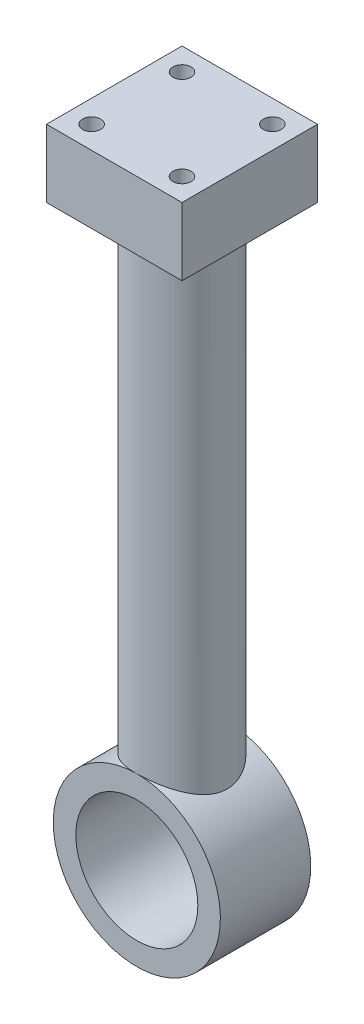
SolidWorks part; units mm, degrees
ref_plane "前视基准面" through (0, 0, 0) normal (0, 0, 1) x (1, 0, 0)
ref_plane "上视基准面" through (0, 0, 0) normal (0, 1, 0) x (1, 0, 0)
ref_plane "右视基准面" through (0, 0, 0) normal (1, 0, 0) x (0, 0, -1)
sketch "草图1" plane through (0, 0, 0) normal (0, 0, 1) x (1, 0, 0)
  circle A0 centre (0, 0) radius 18.5
  circle A1 centre (0, 0) radius 13.5
  dimension "D1" = 37
  dimension "D2" = 27
extrude "凸台-拉伸1" add sketch "草图1" along normal mid plane 20
ref_plane "基准面1" through (0, 123, 0) normal (0, 1, 0) x (1, 0, 0)
sketch "草图3" plane through (0, 123, 0) normal (0, 1, 0) x (1, 0, 0)
  circle A0 centre (0, 0) radius 10
  dimension "D1" = 20
extrude "凸台-拉伸2" add sketch "草图3" against normal up to surface (104.5 mm away)
sketch "草图4" plane through (0, 123, 0) normal (0, 1, 0) x (1, 0, 0)
  line L1 (-15, 15) -> (15, 15)
  line L2 (-15, 15) -> (-15, -15)
  line L3 (-15, -15) -> (15, -15)
  line L4 (15, 15) -> (15, -15)
  line L5 (0, -15) -> (0, 15) construction
  line L6 (-15, 0) -> (15, 0) construction
  point P0 (0, 0)
  dimension "D1" = 30
  dimension "30" = 30
extrude "凸台-拉伸3" add sketch "草图4" along normal blind 15
sketch "草图5" plane through (0, 138, 0) normal (0, 1, 0) x (1, 0, 0)
  line L1 (-10, 10) -> (10, 10) construction
  line L2 (-10, 10) -> (-10, -10) construction
  line L3 (-10, -10) -> (10, -10) construction
  line L4 (10, 10) -> (10, -10) construction
  line L5 (0, -10) -> (0, 10) construction
  line L6 (-10, 0) -> (10, 0) construction
  circle A0 centre (-10, 10) radius 2
  circle A1 centre (10, 10) radius 2
  circle A2 centre (-10, -10) radius 2
  circle A3 centre (10, -10) radius 2
  point P0 (0, 0)
  dimension "D3" = 4
  dimension "D1" = 20
  dimension "D2" = 20
extrude "切除-拉伸1" cut sketch "草图5" against normal blind 15
sketch "草图6" plane through (0, 123, 0) normal (0, -1, 0) x (1, 0, 0)
  line L1 (10, 10) -> (-10, 10) construction
  line L2 (10, 10) -> (10, -10) construction
  line L3 (10, -10) -> (-10, -10) construction
  line L4 (-10, 10) -> (-10, -10) construction
  line L5 (0, -10) -> (0, 10) construction
  line L6 (10, 0) -> (-10, 0) construction
  circle A0 centre (-10, -10) radius 4.5
  circle A1 centre (-10, 10) radius 4.5
  circle A2 centre (10, 10) radius 4.5
  circle A3 centre (10, -10) radius 4.5
  point P3 (0, 0)
  dimension "D1" = 9
extrude "切除-拉伸2" cut sketch "草图6" against normal blind 1.5
